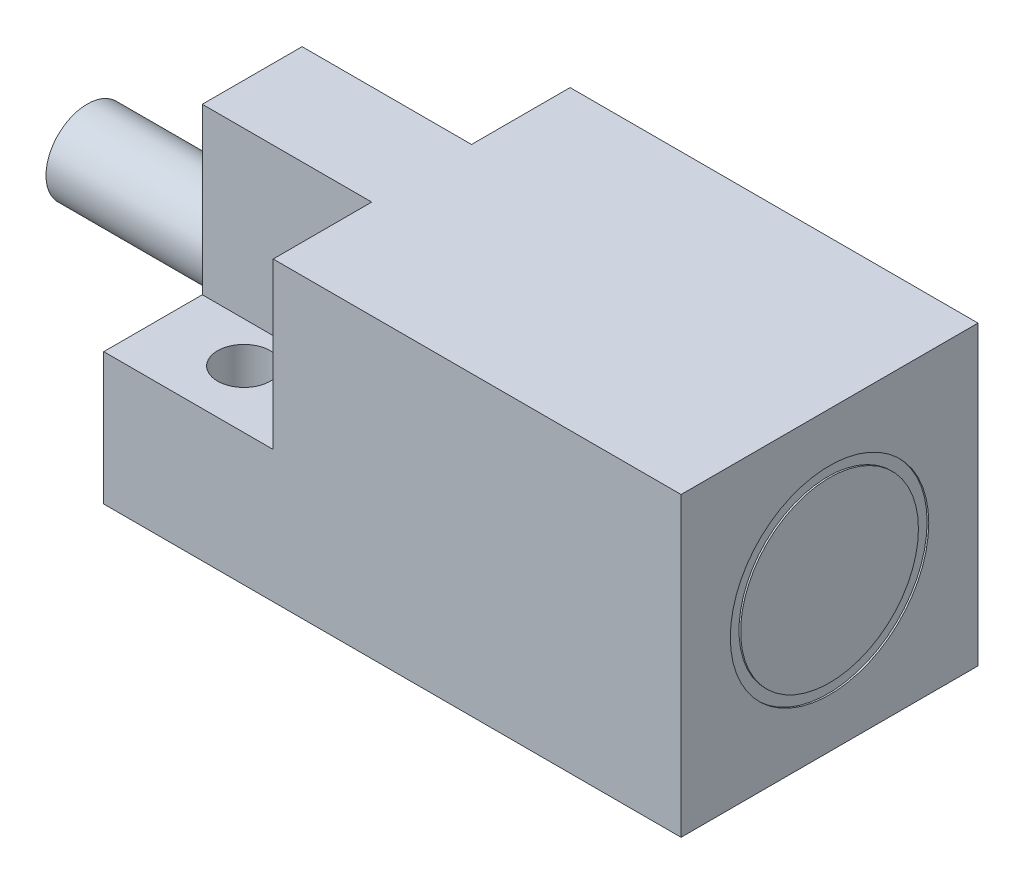
SolidWorks part; units mm, degrees
ref_plane "前视基准面" through (0, 0, 0) normal (0, 0, 1) x (1, 0, 0)
ref_plane "上视基准面" through (0, 0, 0) normal (0, 1, 0) x (1, 0, 0)
ref_plane "右视基准面" through (0, 0, 0) normal (1, 0, 0) x (0, 0, -1)
sketch "草图1" plane through (0, 0, 0) normal (0, 1, 0) x (1, 0, 0)
  line L0 (0, 0) -> (0, 46.6605) construction
  line L1 (-17.5, 9) -> (17.5, 9)
  line L2 (-17.5, 9) -> (-17.5, -9)
  line L3 (-17.5, -9) -> (17.5, -9)
  line L4 (17.5, 9) -> (17.5, -9)
  line L5 (0, 0) -> (35, 0) construction
  dimension "D1" = 35
  dimension "D2" = 18
extrude "凸台-拉伸1" add sketch "草图1" along normal mid plane 18
sketch "草图2" plane through (17.5, 0, 0) normal (1, 0, 0) x (0, 0, -1)
  circle A0 centre (0, 0) radius 6.0157
  circle A1 centre (0, 0) radius 5.3899
extrude "切除-拉伸1" cut sketch "草图2" against normal blind 0.1
sketch "草图3" plane through (0, 9, 0) normal (0, 1, 0) x (1, 0, 0)
  line L0 (0, 0) -> (-17.7585, 0) construction
  line L1 (-17.5, 9) -> (-17.5, -9) construction
  circle A0 centre (-12.5, 5.5) radius 1.6
  circle A1 centre (-12.5, -5.5) radius 1.6
  dimension "D3" = 3.2
  dimension "D1" = 5
  dimension "D2" = 11
extrude "切除-拉伸2" cut sketch "草图3" against normal through all
sketch "草图4" plane through (-17.5, 0, 0) normal (-1, 0, 0) x (0, 0, 1)
  circle A0 centre (0, 0) radius 2.5
  dimension "D1" = 5
extrude "凸台-拉伸2" add sketch "草图4" along normal blind 10
sketch "草图5" plane through (0, 9, 0) normal (0, 1, 0) x (1, 0, 0)
  line L0 (0, 0) -> (-23.0223, 0) construction
  line L1 (-17.5, 9) -> (-7.2289, 9)
  line L2 (-17.5, 9) -> (-17.5, 3.0249)
  line L3 (-17.5, 3.0249) -> (-7.2289, 3.0249)
  line L4 (-7.2289, 9) -> (-7.2289, 3.0249)
  line L5 (-7.2289, -9) -> (-7.2289, -3.0249)
  line L6 (-17.5, -3.0249) -> (-7.2289, -3.0249)
  line L7 (-17.5, -9) -> (-17.5, -3.0249)
  line L8 (-17.5, -9) -> (-7.2289, -9)
extrude "切除-拉伸3" cut sketch "草图5" against normal blind 10
